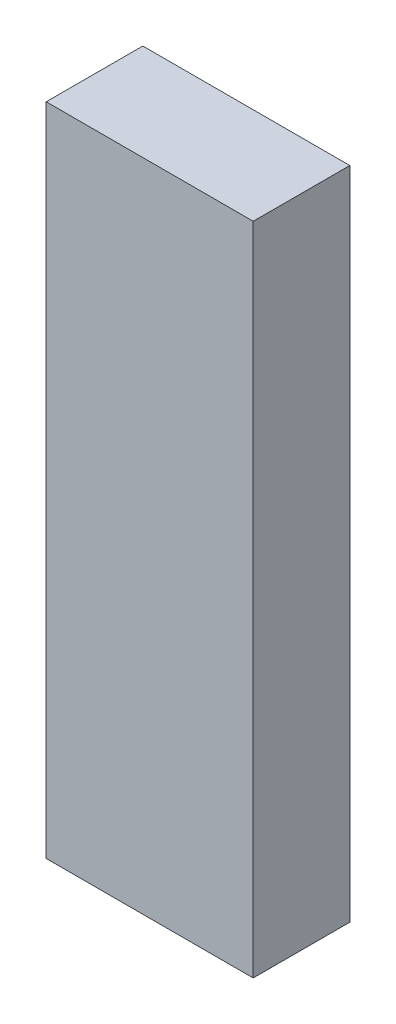
SolidWorks part; units mm, degrees
ref_plane "Front Plane" through (0, 0, 0) normal (0, 0, 1) x (1, 0, 0)
ref_plane "Top Plane" through (0, 0, 0) normal (0, 1, 0) x (1, 0, 0)
ref_plane "Right Plane" through (0, 0, 0) normal (1, 0, 0) x (0, 0, -1)
sketch "Sketch1" plane through (0, 0, 0) normal (0, 1, 0) x (1, 0, 0)
  line L1 (-187.5, -87.5) -> (187.5, -87.5)
  line L2 (-187.5, -87.5) -> (-187.5, 87.5)
  line L3 (-187.5, 87.5) -> (187.5, 87.5)
  line L4 (187.5, -87.5) -> (187.5, 87.5)
  line L5 (-187.5, -87.5) -> (187.5, 87.5) construction
  line L6 (-187.5, 87.5) -> (187.5, -87.5) construction
  point P0 (0, 0)
  dimension "D1" = 375
  dimension "D2" = 175
extrude "Boss-Extrude1" add sketch "Sketch1" along normal blind 1187.25
